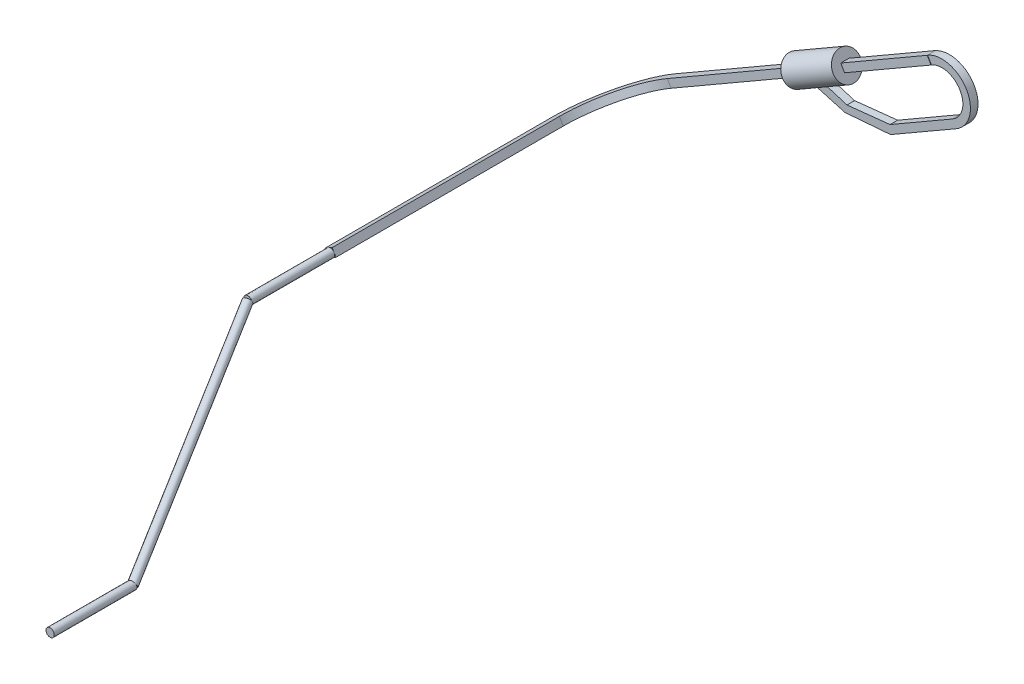
SolidWorks part; units mm, degrees
ref_plane "Front Plane" through (0, 0, 0) normal (0, 0, 1) x (1, 0, 0)
ref_plane "Top Plane" through (0, 0, 0) normal (0, 1, 0) x (1, 0, 0)
ref_plane "Right Plane" through (0, 0, 0) normal (1, 0, 0) x (0, 0, -1)
sketch3d "Plane points - Tendon captive tail"
  point P0 (9.2349, 11.8202, 25.9599)
  point P1 (27.0597, 9.315, 25.9599)
  point P2 (11.74, 29.645, 25.9599)
ref_plane "Drilling plane - Tendon captive tail" through (0, 0, 25.9599) normal (0, 0, 1) x (1, 0, 0)
sketch "S01 - Tendon captive tail" plane through (0, 0, 25.9599) normal (0, 0, 1) x (1, 0, 0)
  circle A0 centre (9.2349, 11.8202) radius 0.6
  dimension "D1" = 1.2
  dimension "D2" = 9.2349
  dimension "D3" = 11.8202
extrude "01 - Tendon captive tail" add sketch "S01 - Tendon captive tail" along normal blind 12
sketch3d "Plane points - Crossed tendon"
  point P0 (0, 30, 0)
  point P1 (16.0482, 38.1521, 0)
  point P2 (-6.4109, 42.6204, 11.1187)
ref_plane "Drilling plane - Crossed tendon" through (-4.6221, 9.099, -12.9929) normal (0.2798, -0.5507, 0.7864) x (0.9601, 0.1605, -0.2292)
sketch "S02 - Crossed tendon" plane through (-4.6221, 9.099, -12.9929) normal (0.2798, -0.5507, 0.7864) x (0.9601, 0.1605, -0.2292)
  circle A0 centre (4.8143, 24.5734) radius 0.6
  dimension "D1" = 1.2
  dimension "D2" = 4.8143
  dimension "D3" = 24.5734
extrude "02 - Crossed tendon" add sketch "S02 - Crossed tendon" along normal blind 33.0107
sketch3d "Plane points - Tendon through rear grommet"
  point P0 (0, 30, -12)
  point P1 (18, 30, -12)
  point P2 (0, 48, -12)
ref_plane "Drilling plane - Tendon through rear grommet" through (0, 0, -12) normal (0, 0, 1) x (1, 0, 0)
sketch "S03 - Tendon through rear grommet" plane through (0, 0, -12) normal (0, 0, 1) x (1, 0, 0)
  circle A0 centre (0, 30) radius 0.6
  dimension "D1" = 1.2
  dimension "D2" = 30
extrude "03 - Tendon through rear grommet" add sketch "S03 - Tendon through rear grommet" along normal blind 12
sketch3d "Plane points - Tendon return"
  point P0 (7.7942, 34.5, -45)
  point P1 (23.3827, 43.5, -45)
  point P2 (7.7942, 34.5, -27)
ref_plane "Drilling plane - Tendon return" through (-12.9904, 22.5, 0) normal (0.5, -0.866, 0) x (-0.866, -0.5, 0)
sketch "S04 - Tendon return" plane through (-12.9904, 22.5, 0) normal (0.5, -0.866, 0) x (-0.866, -0.5, 0)
  line L0 (-14.4, 12) -> (-14.4, 45)
  line L1 (-24, 54.6) -> (-67.5985, 54.6)
  line L2 (-67.5985, 54.6) -> (-67.5985, 53.4)
  line L3 (-67.5985, 53.4) -> (-24, 53.4)
  line L4 (-15.6, 45) -> (-15.6, 12)
  line L5 (-15.6, 12) -> (-14.4, 12)
  arc A0 (-14.4, 45) -> (-24, 54.6) centre (-24, 45) ccw
  arc A1 (-24, 53.4) -> (-15.6, 45) centre (-24, 45) cw
  dimension "D1" = 9.6
  dimension "D2" = 8.4
  dimension "D3" = 14.4
  dimension "D4" = 67.5985
  dimension "D5" = 12
  dimension "D6" = 53.4
extrude "04 - Tendon return" add sketch "S04 - Tendon return" along normal blind 1.1 from offset 0.55
sketch3d "Plane points - Removable backed eye around polished clevis sleeve"
  point P0 (47.3516, 53.1816, -54)
  point P1 (62.9401, 62.1816, -54)
  point P2 (38.3516, 68.77, -54)
ref_plane "Drilling plane - Removable backed eye around polished clevis sleeve" through (0, 0, -54) normal (0, 0, 1) x (1, 0, 0)
sketch "S05 - Removable backed eye around polished clevis sleeve" plane through (0, 0, -54) normal (0, 0, 1) x (1, 0, 0)
  line L0 (45.1034, 56.6756) -> (45.2766, 56.7756)
  line L1 (49.4266, 49.5876) -> (39.9004, 44.0876)
  line L2 (39.9004, 44.0876) -> (33.2792, 43.5557)
  line L3 (33.2792, 43.5557) -> (27.7651, 45.1064)
  line L4 (27.7651, 45.1064) -> (28.2311, 46.2993)
  line L5 (28.2311, 46.2993) -> (33.572, 44.6485)
  line L6 (33.572, 44.6485) -> (39.8267, 45.3152)
  line L7 (39.8267, 45.3152) -> (48.8766, 50.5402)
  line L8 (45.8266, 55.8229) -> (45.6534, 55.7229)
  line L9 (45.6534, 55.7229) -> (45.1034, 56.6756)
  arc A0 (45.2766, 56.7756) -> (49.4266, 49.5876) centre (47.3516, 53.1816) cw
  arc A1 (48.8766, 50.5402) -> (45.8266, 55.8229) centre (47.3516, 53.1816) ccw
  dimension "D1" = 4.15
  dimension "D2" = 3.05
  dimension "D3" = 27.7651
  dimension "D4" = 28.2311
  dimension "D5" = 33.2792
  dimension "D6" = 33.572
  dimension "D7" = 39.8267
  dimension "D8" = 39.9004
  dimension "D9" = 45.1034
  dimension "D10" = 45.2766
  dimension "D11" = 45.6534
  dimension "D12" = 45.8266
  dimension "D13" = 47.3516
  dimension "D14" = 48.8766
  dimension "D15" = 49.4266
  dimension "D16" = 43.5557
  dimension "D17" = 44.0876
  dimension "D18" = 44.6485
  dimension "D19" = 45.1064
  dimension "D20" = 45.3152
  dimension "D21" = 46.2993
  dimension "D22" = 49.5876
  dimension "D25" = 55.7229
  dimension "D27" = 56.6756
extrude "05 - Removable backed eye around polished clevis sleeve" add sketch "S05 - Removable backed eye around polished clevis sleeve" along normal blind 1.1 from offset 0.55
sketch3d "Plane points - Dressed eye knot envelope"
  point P0 (25.6331, 44.7993, -54)
  point P1 (16.6331, 60.3877, -54)
  point P2 (25.6331, 44.7993, -36)
ref_plane "Drilling plane - Dressed eye knot envelope" through (38.6234, 22.2993, 0) normal (0.866, 0.5, 0) x (0, 0, -1)
sketch "S06 - Dressed eye knot envelope" plane through (38.6234, 22.2993, 0) normal (0.866, 0.5, 0) x (0, 0, -1)
  circle A0 centre (54, 25.9808) radius 2
  dimension "D1" = 4
  dimension "D2" = 54
  dimension "D3" = 25.9808
extrude "06 - Dressed eye knot envelope" add sketch "S06 - Dressed eye knot envelope" along normal blind 8.5
